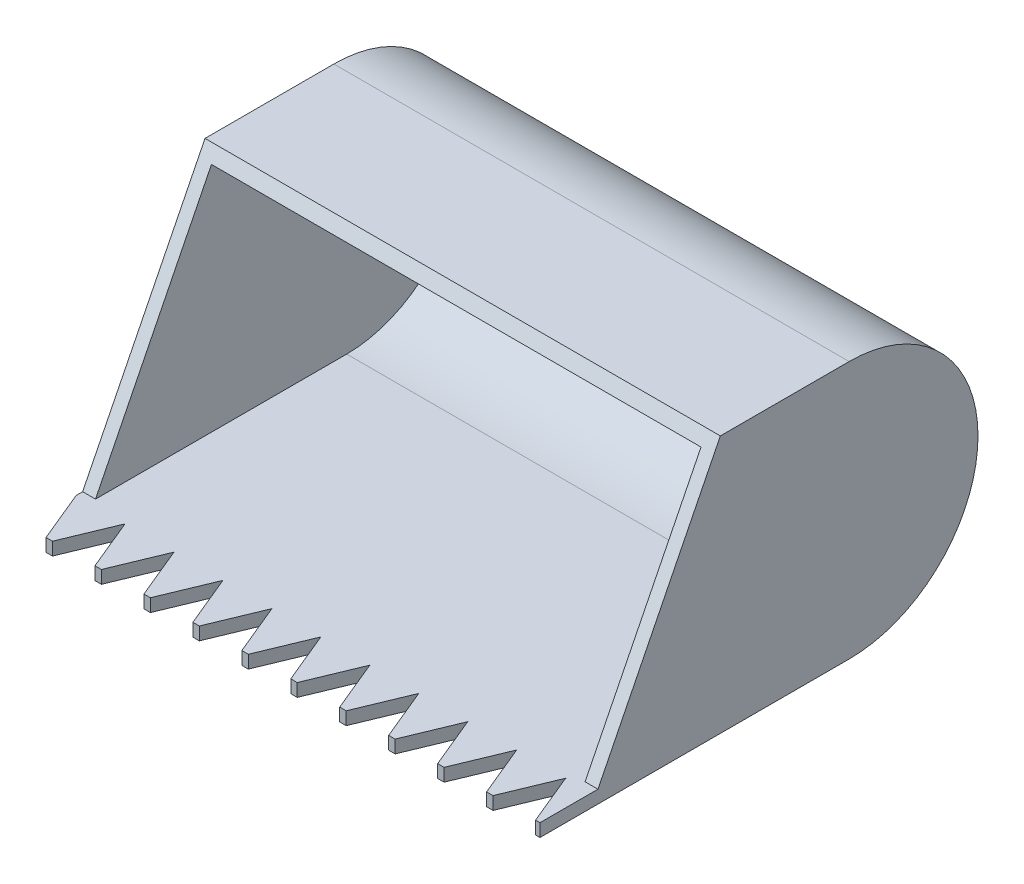
SolidWorks part; units mm, degrees
ref_plane "Front Plane" through (0, 0, 0) normal (0, 0, 1) x (1, 0, 0)
ref_plane "Top Plane" through (0, 0, 0) normal (0, 1, 0) x (1, 0, 0)
ref_plane "Right Plane" through (0, 0, 0) normal (1, 0, 0) x (0, 0, -1)
sketch "Sketch1" plane through (0, 0, 0) normal (0, 0, 1) x (1, 0, 0)
  line L0 (0, 0) -> (0, 50.8)
  line L1 (0, 50.8) -> (101.6, 50.8)
  line L2 (101.6, 50.8) -> (101.6, 0)
  line L3 (101.6, 0) -> (0, 0)
  dimension "D1" = 101.6
  dimension "D2" = 50.8
extrude "Boss-Extrude1" add sketch "Sketch1" against normal blind 50.8 contours L1 L2 L3 L0
sketch "Sketch2" plane through (0, 0, 0) normal (-1, 0, 0) x (0, 0, 1)
  line L0 (-50.8, 0) -> (-50.8, 50.8) construction
  line L1 (-50.8, 50.8) -> (-50.8, 0)
  arc A0 (-50.8, 50.8) -> (-50.8, 0) centre (-50.8, 25.4) ccw
extrude "Boss-Extrude2" add sketch "Sketch2" against normal up to surface (101.6 mm away) up to face at (101.6, 25.4, -25.4)
sketch "Sketch3" plane through (0, 0, 0) normal (-1, 0, 0) x (0, 0, 1)
  line L0 (0, 0) -> (-25.4, 50.8)
  line L1 (-50.8, 50.8) -> (0, 50.8) construction
  line L2 (-25.4, 50.8) -> (0, 50.8)
  line L3 (0, 50.8) -> (0, 0)
extrude "Cut-Extrude1" cut sketch "Sketch3" against normal up to surface (101.6 mm away) up to face at (101.6, 25.4, -31.75)
shell "Shell1" thickness 2.54
ref_plane "Plane1" through (0, 0, -2.54) normal (0, 0, 1) x (1, 0, 0)
sketch "Sketch4" plane through (0, 0, -2.54) normal (0, 0, 1) x (1, 0, 0)
  line L0 (0, 2.54) -> (101.6, 2.54)
  line L1 (0, 50.8) -> (0, 0) construction
  line L2 (101.6, 0) -> (101.6, 50.8) construction
  line L3 (101.6, 2.54) -> (101.6, 0)
  line L4 (101.6, 0) -> (0, 0) construction
  line L5 (101.6, 0) -> (0, 0)
  line L6 (0, 0) -> (0, 2.54)
  dimension "D1" = 2.54
extrude "Boss-Extrude3" add sketch "Sketch4" along normal blind 12.7
sketch "Sketch5" plane through (0, 2.54, 0) normal (0, 1, 0) x (1, 0, 0)
  line L0 (0, 0) -> (4.2084, -10.16)
  line L1 (5.4784, -10.16) -> (9.6868, 0)
  line L3 (4.2084, -10.16) -> (0, -10.16)
  line L4 (0, -10.16) -> (0, 0)
  line L8 (101.6, -10.16) -> (0, -10.16) construction
  line L9 (9.6868, 0) -> (9.6868, -10.16)
  line L10 (9.6868, -10.16) -> (5.4784, -10.16)
  dimension "D1" = 45
  dimension "D2" = 1.27
extrude "Cut-Extrude2" cut sketch "Sketch5" against normal up to surface (2.54 mm away) up to face at (50.8, 0, -20.32)
pattern_linear "LPattern1" count 11 spacing 9.652 along (1, 0, 0) of "Cut-Extrude2"
